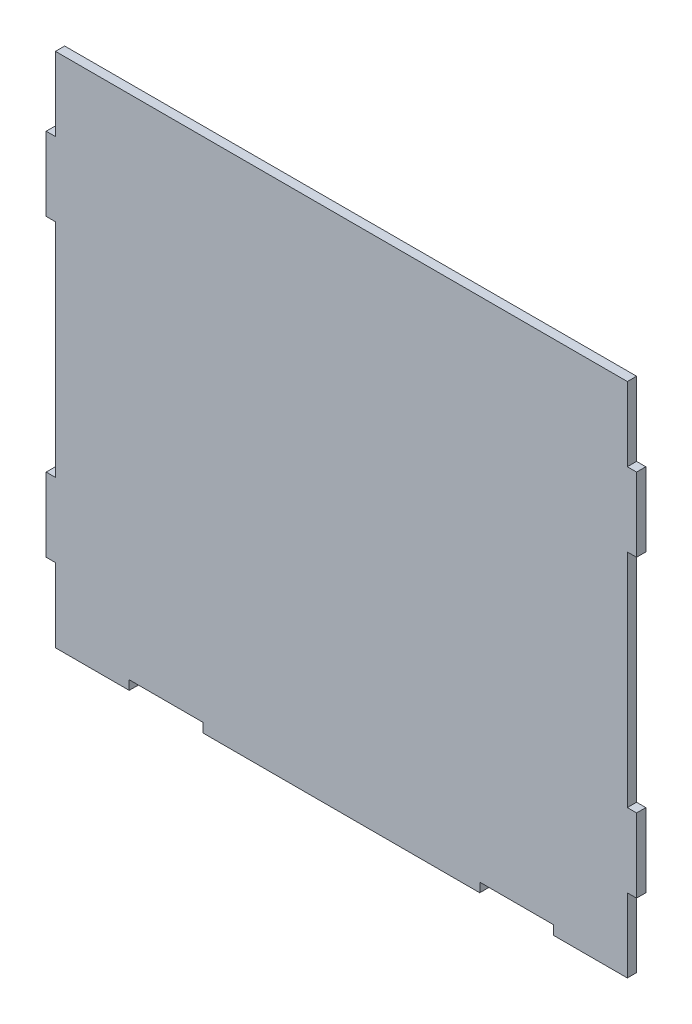
SolidWorks part; units mm, degrees
ref_plane "Front Plane" through (0, 0, 0) normal (0, 0, 1) x (1, 0, 0)
ref_plane "Top Plane" through (0, 0, 0) normal (0, 1, 0) x (1, 0, 0)
ref_plane "Right Plane" through (0, 0, 0) normal (1, 0, 0) x (0, 0, -1)
sketch "Sketch1" plane through (0, 0, 0) normal (0, 0, 1) x (1, 0, 0)
  line L0 (0, 177.8) -> (0, 152.4)
  line L1 (0, 152.4) -> (-3.175, 152.4)
  line L2 (-3.175, 152.4) -> (-3.175, 127)
  line L3 (0, 177.8) -> (196.85, 177.8)
  line L4 (196.85, 177.8) -> (196.85, 152.4)
  line L5 (196.85, 152.4) -> (200.025, 152.4)
  line L6 (200.025, 152.4) -> (200.025, 127)
  line L7 (200.025, 127) -> (196.85, 127)
  line L8 (196.85, 127) -> (196.85, 50.8)
  line L9 (196.85, 50.8) -> (200.025, 50.8)
  line L10 (200.025, 50.8) -> (200.025, 25.4)
  line L11 (200.025, 25.4) -> (196.85, 25.4)
  line L12 (196.85, 25.4) -> (196.85, 0)
  line L13 (0, 0) -> (25.4, 0)
  line L29 (-3.175, 127) -> (0, 127)
  line L30 (0, 127) -> (0, 50.8)
  line L31 (0, 50.8) -> (-3.175, 50.8)
  line L32 (-3.175, 50.8) -> (-3.175, 25.4)
  line L33 (-3.175, 25.4) -> (0, 25.4)
  line L34 (0, 25.4) -> (0, 0)
  line L35 (25.4, 0) -> (25.4, 3.175)
  line L36 (25.4, 3.175) -> (50.8, 3.175)
  line L37 (50.8, 3.175) -> (50.8, 0)
  line L38 (50.8, 0) -> (146.05, 0)
  line L39 (146.05, 0) -> (146.05, 3.175)
  line L40 (146.05, 3.175) -> (171.45, 3.175)
  line L41 (171.45, 3.175) -> (171.45, 0)
  line L42 (171.45, 0) -> (196.85, 0)
  dimension "D2" = 196.85
  dimension "D3" = 25.4
  dimension "D4" = 25.4
  dimension "D7" = 3.175
  dimension "D8" = 25.4
  dimension "D9" = 25.4
  dimension "D10" = 76.2
extrude "Boss-Extrude1" add sketch "Sketch1" along normal blind 3.175
